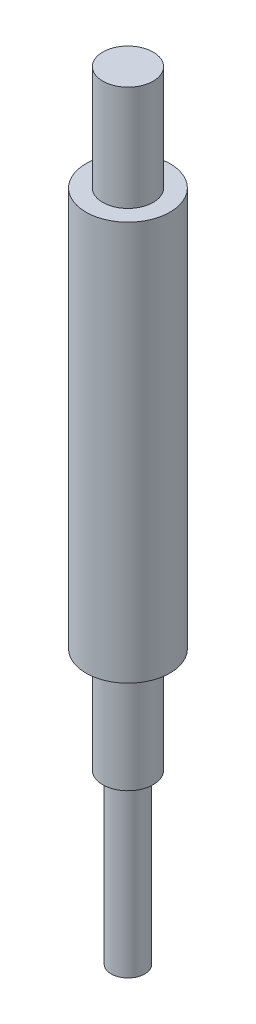
SolidWorks part; units mm, degrees
ref_plane "Спереди" through (0, 0, 0) normal (0, 0, 1) x (1, 0, 0)
ref_plane "Сверху" through (0, 0, 0) normal (0, 1, 0) x (1, 0, 0)
ref_plane "Справа" through (0, 0, 0) normal (1, 0, 0) x (0, 0, -1)
sketch "Эскиз2" plane through (0, 0, 0) normal (0, 1, 0) x (1, 0, 0)
  circle A0 centre (0, 0) radius 4
extrude "Бобышка-Вытянуть1" add sketch "Эскиз2" along normal blind 40
sketch "Эскиз3" plane through (0, 40, 0) normal (0, 1, 0) x (1, 0, 0)
  circle A0 centre (0, 0) radius 6
extrude "Бобышка-Вытянуть3" add sketch "Эскиз3" along normal blind 25 contours A0
sketch "Эскиз4" plane through (0, 65, 0) normal (0, 1, 0) x (1, 0, 0)
  circle A0 centre (0, 0) radius 10
extrude "Бобышка-Вытянуть4" add sketch "Эскиз4" along normal blind 95
sketch "Эскиз5" plane through (0, 160, 0) normal (0, 1, 0) x (1, 0, 0)
  circle A0 centre (0, 0) radius 6
extrude "Бобышка-Вытянуть5" add sketch "Эскиз5" along normal blind 25 contours A0
